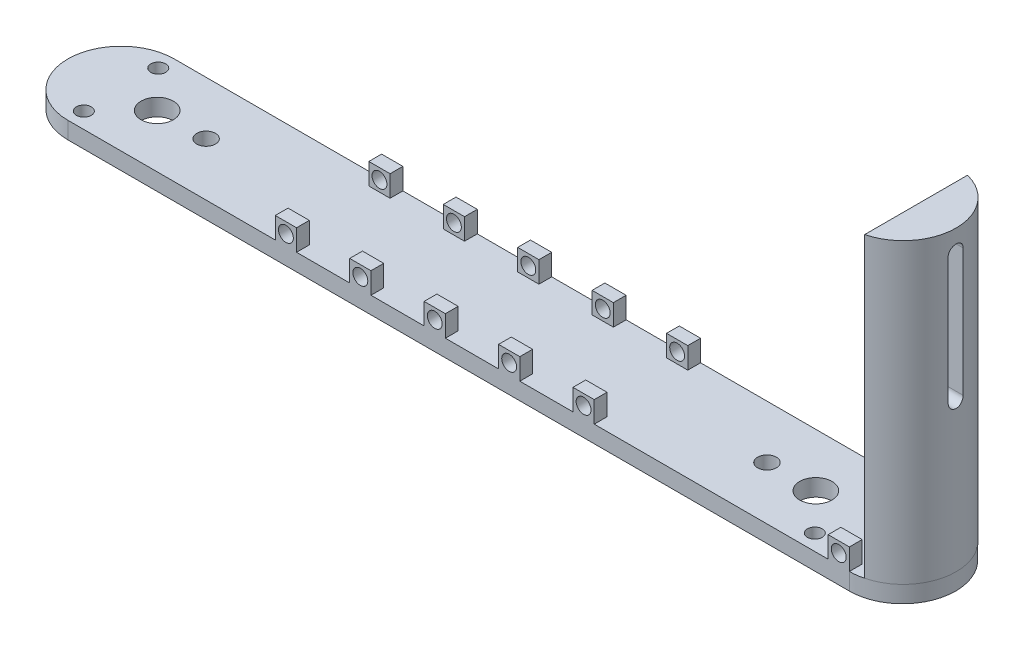
SolidWorks part; units mm, degrees
ref_plane "Front Plane" through (0, 0, 0) normal (0, 0, 1) x (1, 0, 0)
ref_plane "Top Plane" through (0, 0, 0) normal (0, 1, 0) x (1, 0, 0)
ref_plane "Right Plane" through (0, 0, 0) normal (1, 0, 0) x (0, 0, -1)
sketch "Sketch1" plane through (0, 0, 0) normal (0, 1, 0) x (1, 0, 0)
  line L0 (-91.885, 0) -> (91.885, 0) construction
  line L1 (-91.885, 12.5) -> (91.885, 12.5)
  line L2 (-91.885, -12.5) -> (91.885, -12.5)
  arc A0 (-91.885, 12.5) -> (-91.885, -12.5) centre (-91.885, 0) ccw
  arc A1 (91.885, -12.5) -> (91.885, 12.5) centre (91.885, 0) ccw
  circle A4 centre (71.5, 0) radius 3.8
  circle A5 centre (-91.885, 8.75) radius 1.75
  circle A6 centre (-91.885, -8.75) radius 1.75
  circle A7 centre (-83.385, 0) radius 3.8
  circle A8 centre (-71.885, 0) radius 2.2
  circle A9 centre (60, 0) radius 2.2
  circle A10 centre (80, 8.75) radius 1.75
  circle A11 centre (80, -8.75) radius 1.75
  point P2 (0, 0)
  dimension "D2" = 25
  dimension "D3" = 17.5
  dimension "D4" = 0
  dimension "D7" = 7.6
  dimension "D11" = 3.5
  dimension "D12" = 3.5
  dimension "D13" = 7.6
  dimension "D17" = 4.4
  dimension "D18" = 4.4
  dimension "D23" = 3.5
  dimension "D24" = 3.5
  dimension "D8" = 11.5
  dimension "D9" = 60
  dimension "D10" = 0
  dimension "D14" = 8.5
  dimension "D15" = 3.75
  dimension "D16" = 17.5
  dimension "D19" = 11.5
  dimension "D21" = 3.75
  dimension "D26" = 8.5
  dimension "D27" = 3.75
extrude "Boss-Extrude1" add sketch "Sketch1" along normal blind 4
sketch "Sketch2" plane through (0, 4, 0) normal (0, 1, 0) x (1, 0, 0)
  line L1 (95.0738, -12.0864) -> (95.0738, 12.0864)
  arc A1 (91.885, -12.5) -> (91.885, 12.5) centre (91.885, 0) ccw construction
  arc A3 (95.0738, 12.0864) -> (95.0738, -12.0864) centre (92.0324, 0) cw
extrude "Boss-Extrude2" add sketch "Sketch2" along normal blind 70
sketch "Sketch5" plane through (95.0738, 0, 0) normal (-1, 0, 0) x (0, 0, 1)
  line L0 (0, 39) -> (0, 69) construction
  line L2 (-1.75, 39) -> (-1.75, 69)
  line L3 (1.75, 39) -> (1.75, 69)
  line L4 (-12.0864, 74) -> (12.0864, 74) construction
  arc A2 (-1.75, 39) -> (1.75, 39) centre (0, 39) ccw
  arc A3 (1.75, 69) -> (-1.75, 69) centre (0, 69) ccw
  point P9 (0, 54)
  dimension "D5" = 30
  dimension "D6" = 3.5
  dimension "D7" = 20
extrude "Cut-Extrude1" cut sketch "Sketch5" against normal blind 17 and the other way blind 10
sketch "Sketch6" plane through (0, 4, 0) normal (0, 1, 0) x (1, 0, 0)
  line L0 (86.885, -12.5) -> (86.885, -9.5)
  line L1 (-91.885, -12.5) -> (91.885, -12.5) construction
  line L2 (86.885, -9.5) -> (91.885, -9.5)
  line L3 (91.885, -9.5) -> (91.885, -12.5)
  line L4 (26.885, -12.5) -> (26.885, -9.5)
  line L5 (26.885, -9.5) -> (31.885, -9.5)
  line L6 (31.885, -9.5) -> (31.885, -12.5)
  line L7 (9.385, -12.5) -> (9.385, -9.5)
  line L8 (9.385, -9.5) -> (14.385, -9.5)
  line L9 (14.385, -9.5) -> (14.385, -12.5)
  line L10 (-8.115, -12.5) -> (-8.115, -9.5)
  line L11 (-8.115, -9.5) -> (-3.115, -9.5)
  line L12 (-3.115, -9.5) -> (-3.115, -12.5)
  line L13 (-25.615, -12.5) -> (-25.615, -9.5)
  line L14 (-25.615, -9.5) -> (-20.615, -9.5)
  line L15 (-20.615, -9.5) -> (-20.615, -12.5)
  line L16 (-43.115, -12.5) -> (-43.115, -9.5)
  line L17 (-43.115, -9.5) -> (-38.115, -9.5)
  line L18 (-38.115, -9.5) -> (-38.115, -12.5)
  line L19 (-43.115, -12.5) -> (-38.115, -12.5)
  line L20 (-25.615, -12.5) -> (-20.615, -12.5)
  line L21 (-8.115, -12.5) -> (-3.115, -12.5)
  line L22 (9.385, -12.5) -> (14.385, -12.5)
  line L23 (26.885, -12.5) -> (31.885, -12.5)
  line L24 (86.885, -12.5) -> (91.885, -12.5)
  line L25 (86.885, 9.5) -> (86.885, 12.5)
  line L26 (86.885, 12.5) -> (91.885, 12.5)
  line L27 (91.885, 12.5) -> (91.885, 9.5)
  line L28 (26.885, 9.5) -> (26.885, 12.5)
  line L29 (26.885, 12.5) -> (31.885, 12.5)
  line L30 (31.885, 12.5) -> (31.885, 9.5)
  line L31 (9.385, 9.5) -> (9.385, 12.5)
  line L32 (9.385, 12.5) -> (14.385, 12.5)
  line L33 (14.385, 12.5) -> (14.385, 9.5)
  line L34 (-8.115, 9.5) -> (-8.115, 12.5)
  line L35 (-8.115, 12.5) -> (-3.115, 12.5)
  line L36 (-3.115, 12.5) -> (-3.115, 9.5)
  line L37 (-25.615, 9.5) -> (-25.615, 12.5)
  line L38 (-25.615, 12.5) -> (-20.615, 12.5)
  line L39 (-20.615, 12.5) -> (-20.615, 9.5)
  line L40 (-43.115, 9.5) -> (-43.115, 12.5)
  line L41 (-43.115, 12.5) -> (-38.115, 12.5)
  line L42 (-38.115, 12.5) -> (-38.115, 9.5)
  line L43 (-43.115, 9.5) -> (-38.115, 9.5)
  line L44 (-25.615, 9.5) -> (-20.615, 9.5)
  line L45 (-8.115, 9.5) -> (-3.115, 9.5)
  line L46 (9.385, 9.5) -> (14.385, 9.5)
  line L47 (26.885, 9.5) -> (31.885, 9.5)
  line L48 (86.885, 9.5) -> (91.885, 9.5)
  dimension "D1" = 3
  dimension "D2" = 5
  dimension "D3" = 2
  dimension "D5" = 0
  dimension "D4" = 5
  dimension "D6" = 2
extrude "Boss-Extrude4" add sketch "Sketch6" along normal blind 5
sketch "Sketch7" plane through (0, 0, 12.5) normal (0, 0, 1) x (1, 0, 0)
  line L1 (91.885, 9) -> (91.885, 4) construction
  line L2 (86.885, 9) -> (91.885, 9) construction
  circle A0 centre (89.385, 6.5) radius 1.75
  circle A1 centre (29.385, 6.5) radius 1.75
  circle A2 centre (11.885, 6.5) radius 1.75
  circle A3 centre (-5.615, 6.5) radius 1.75
  circle A4 centre (-23.115, 6.5) radius 1.75
  circle A5 centre (-40.615, 6.5) radius 1.75
  dimension "D1" = 3.5
  dimension "D2" = 2.5
  dimension "D3" = 2.5
  dimension "D4" = 2
  dimension "D5" = 5
extrude "Cut-Extrude2" cut sketch "Sketch7" against normal blind 35
